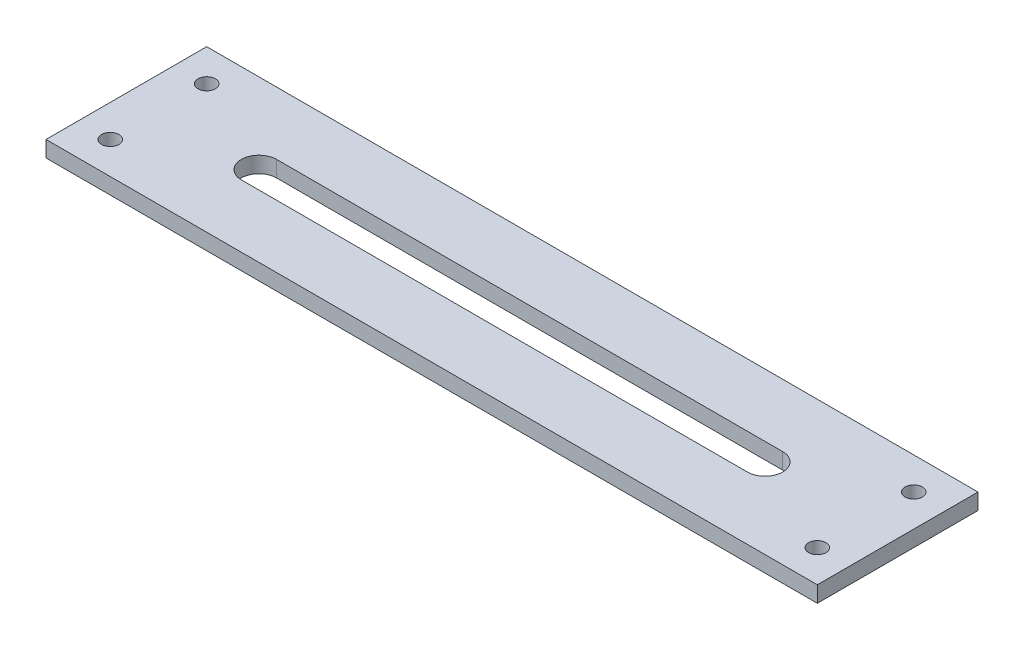
SolidWorks part; units mm, degrees
ref_plane "Front Plane" through (0, 0, 0) normal (0, 0, 1) x (1, 0, 0)
ref_plane "Top Plane" through (0, 0, 0) normal (0, 1, 0) x (1, 0, 0)
ref_plane "Right Plane" through (0, 0, 0) normal (1, 0, 0) x (0, 0, -1)
sketch "Sketch1" plane through (0, 0, 0) normal (0, 1, 0) x (1, 0, 0)
  line L0 (-100, 0) -> (100, 0) construction
  line L1 (152.4, 31.75) -> (-152.4, 31.75)
  line L2 (152.4, 31.75) -> (152.4, -31.75)
  line L3 (152.4, -31.75) -> (-152.4, -31.75)
  line L4 (-152.4, 31.75) -> (-152.4, -31.75)
  line L5 (152.4, 31.75) -> (-152.4, -31.75) construction
  line L6 (152.4, -31.75) -> (-152.4, 31.75) construction
  line L7 (-100, 6.985) -> (100, 6.985)
  line L8 (-100, -6.985) -> (100, -6.985)
  line L9 (0, 0) -> (0, 31.75) construction
  line L10 (-152.4, 0) -> (-106.985, 0) construction
  arc A0 (-100, 6.985) -> (-100, -6.985) centre (-100, 0) ccw
  arc A1 (100, -6.985) -> (100, 6.985) centre (100, 0) ccw
  circle A2 centre (-139.7, 19.05) radius 3.429
  circle A3 centre (139.7, 19.05) radius 3.429
  circle A4 centre (139.7, -19.05) radius 3.429
  circle A5 centre (-139.7, -19.05) radius 3.429
  point P0 (0, 0)
  point P8 (0, 0)
  dimension "D5" = 6.858
  dimension "D1" = 304.8
  dimension "D2" = 63.5
  dimension "D3" = 200
  dimension "D4" = 13.97
  dimension "D6" = 12.7
  dimension "D7" = 12.7
extrude "Boss-Extrude1" add sketch "Sketch1" along normal blind 6.35
